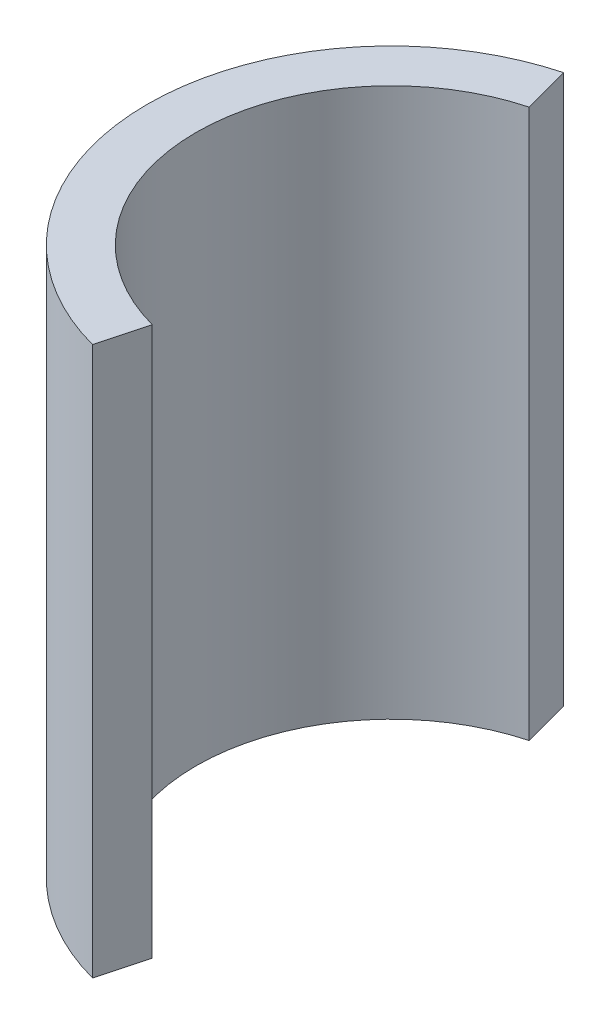
SolidWorks part; units mm, degrees
ref_plane "Front Plane" through (0, 0, 0) normal (0, 0, 1) x (1, 0, 0)
ref_plane "Top Plane" through (0, 0, 0) normal (0, 1, 0) x (1, 0, 0)
ref_plane "Right Plane" through (0, 0, 0) normal (1, 0, 0) x (0, 0, -1)
sketch "Sketch1" plane through (0, 0, 0) normal (0, 1, 0) x (1, 0, 0)
  line L0 (-5.1764, 19.3185) -> (0, 0) construction
  line L1 (-4.1411, -15.4548) -> (-5.1764, -19.3185)
  line L2 (0, 0) -> (0, 50000) construction
  line L3 (-5.1764, 19.3185) -> (-4.1411, 15.4548)
  circle A0 centre (0, 0) radius 20 construction
  arc A1 (-5.1764, 19.3185) -> (-5.1764, -19.3185) centre (0, 0) ccw
  arc A2 (-4.1411, 15.4548) -> (-4.1411, -15.4548) centre (0, 0) ccw
  dimension "D1" = 40
  dimension "D3" = 20
  dimension "D2" = 15
  dimension "D4" = 4
extrude "Boss-Extrude1" add sketch "Sketch1" along normal mid plane 45
